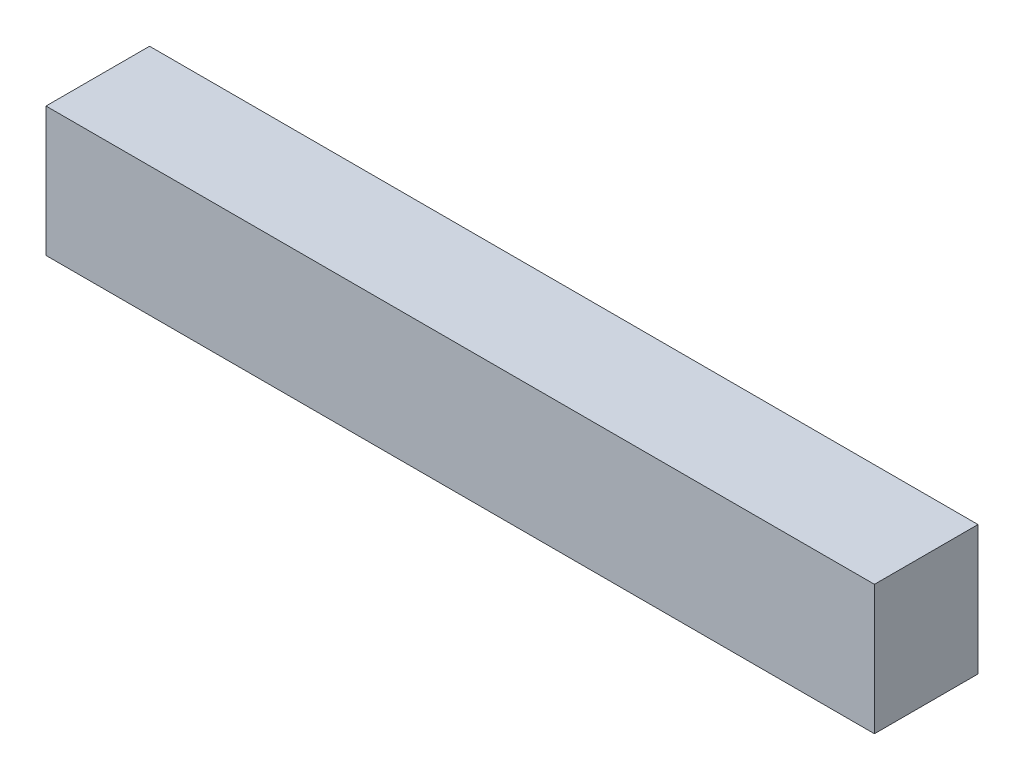
SolidWorks part; units mm, degrees
ref_plane "Front Plane" through (0, 0, 0) normal (0, 0, 1) x (1, 0, 0)
ref_plane "Top Plane" through (0, 0, 0) normal (0, 1, 0) x (1, 0, 0)
ref_plane "Right Plane" through (0, 0, 0) normal (1, 0, 0) x (0, 0, -1)
sketch "Sketch1" plane through (0, 0, 0) normal (0, 1, 0) x (1, 0, 0)
  line L1 (-16, -2) -> (16, -2)
  line L2 (-16, -2) -> (-16, 2)
  line L3 (-16, 2) -> (16, 2)
  line L4 (16, -2) -> (16, 2)
  line L5 (-16, -2) -> (16, 2) construction
  line L6 (-16, 2) -> (16, -2) construction
  point P0 (0, 0)
  dimension "D1" = 4
  dimension "D2" = 32
extrude "Boss-Extrude1" add sketch "Sketch1" along normal blind 5
